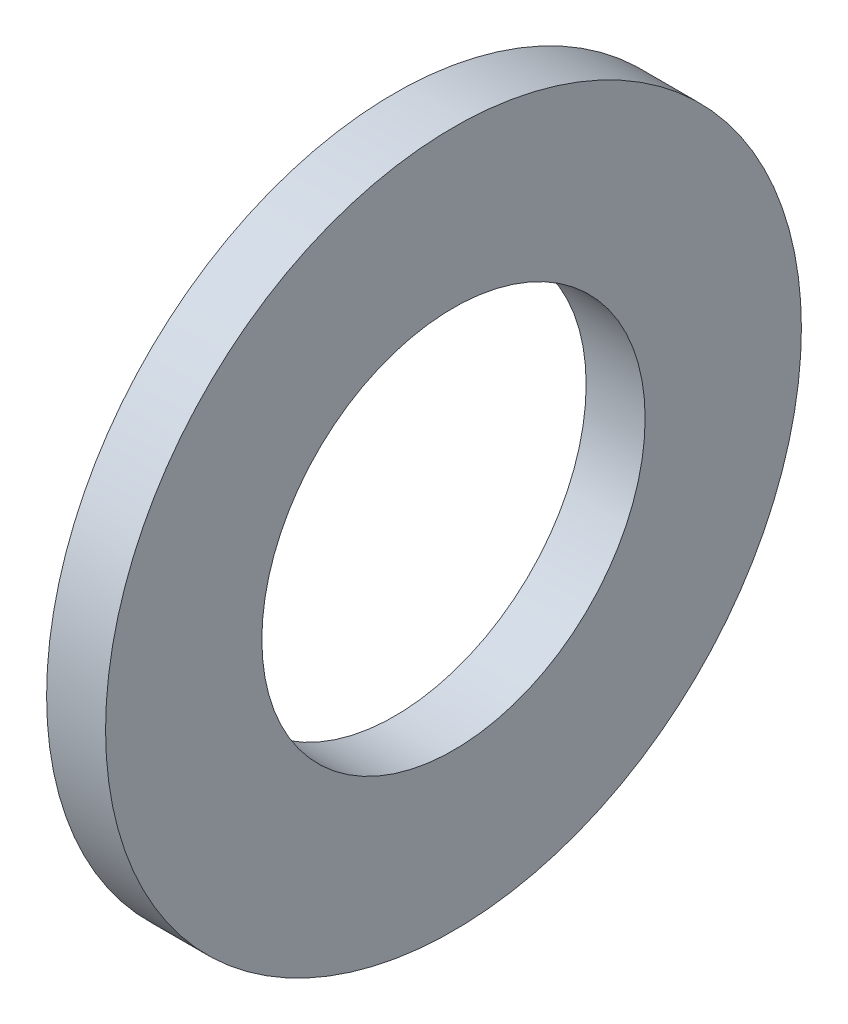
SolidWorks part; units mm, degrees
ref_plane "Front Plane" through (0, 0, 0) normal (0, 0, 1) x (1, 0, 0)
ref_plane "Top Plane" through (0, 0, 0) normal (0, 1, 0) x (1, 0, 0)
ref_plane "Right Plane" through (0, 0, 0) normal (1, 0, 0) x (0, 0, -1)
sketch "Sketch1" plane through (0, 0, 0) normal (1, 0, 0) x (0, 0, -1)
  circle A0 centre (0, 0) radius 3.25
  circle A1 centre (0, 0) radius 5.9
extrude "Boss-Extrude1" add sketch "Sketch1" along normal blind 1
